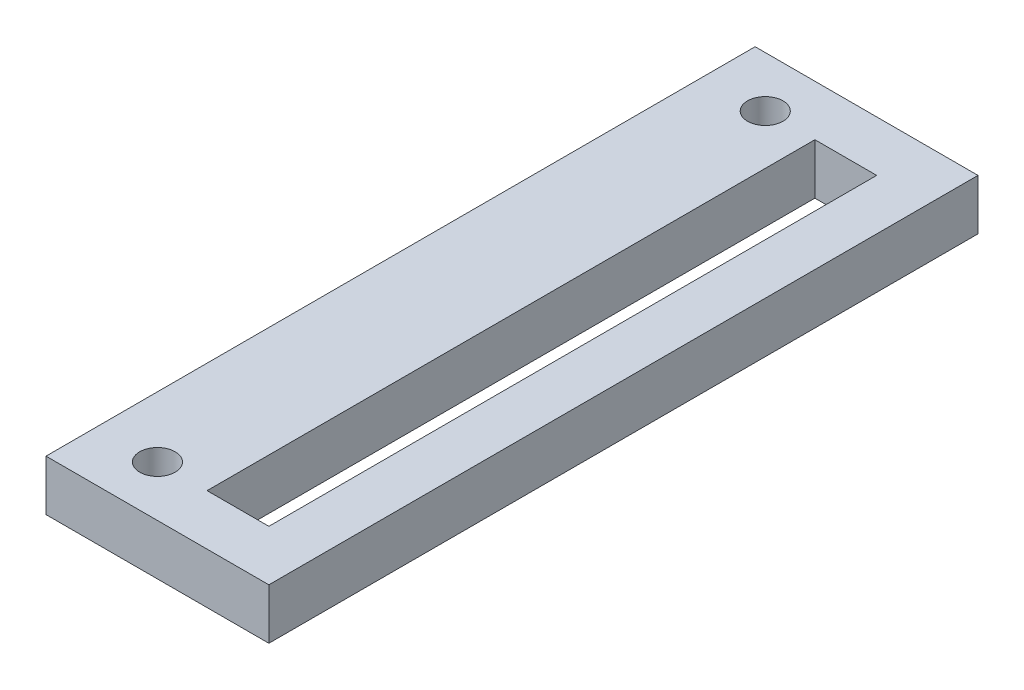
SolidWorks part; units mm, degrees
ref_plane "Front Plane" through (0, 0, 0) normal (0, 0, 1) x (1, 0, 0)
ref_plane "Top Plane" through (0, 0, 0) normal (0, 1, 0) x (1, 0, 0)
ref_plane "Right Plane" through (0, 0, 0) normal (1, 0, 0) x (0, 0, -1)
sketch "Sketch1" plane through (0, 0, 0) normal (0, 1, 0) x (1, 0, 0)
  line L0 (-1000, 35) -> (49000, 35) construction
  line L1 (0, 0) -> (22, 0)
  line L2 (0, 0) -> (0, 70)
  line L3 (0, 70) -> (22, 70)
  line L4 (22, 0) -> (22, 70)
  line L6 (17, 65) -> (10.9, 65)
  line L7 (17, 65) -> (17, 5)
  line L8 (17, 5) -> (10.9, 5)
  line L9 (10.9, 65) -> (10.9, 5)
  circle A0 centre (6, 65) radius 1.75
  circle A1 centre (6, 5) radius 1.75
  point P10 (0, 35)
  point P16 (17, 35)
  dimension "D3" = 3.5
  dimension "D4" = 60
  dimension "D1" = 70
  dimension "D2" = 22
  dimension "D5" = 6
  dimension "D6" = 6.1
  dimension "D7" = 5
  dimension "D8" = 60
extrude "Boss-Extrude1" add sketch "Sketch1" along normal blind 5
